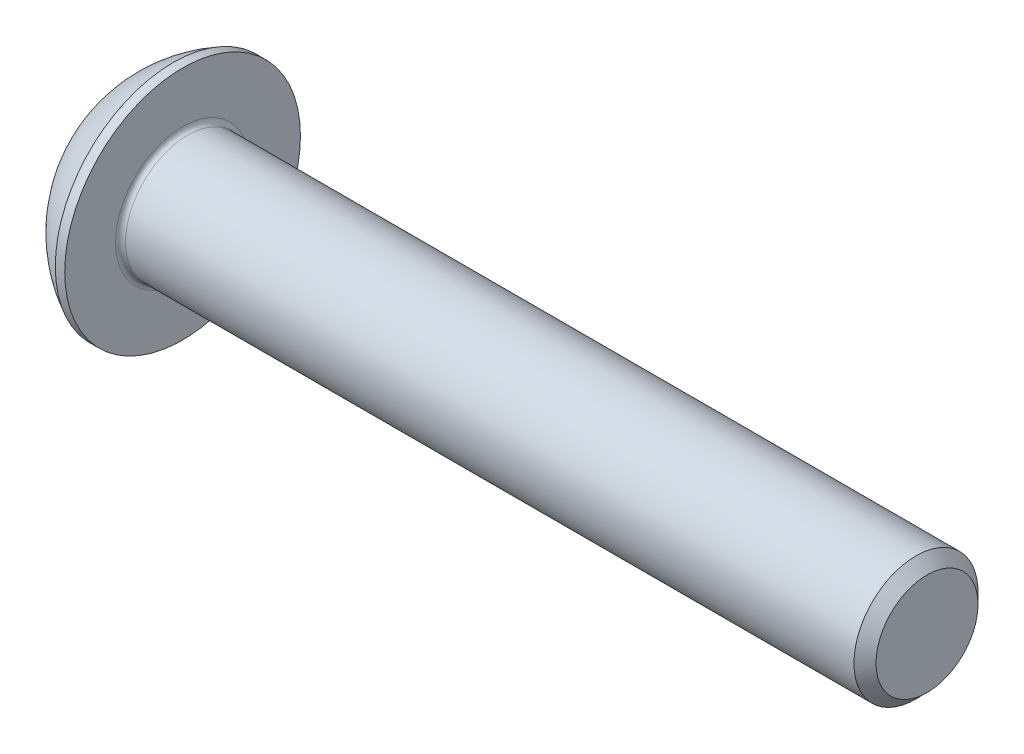
SolidWorks part; units mm, degrees
ref_plane "Plane1" through (0, 0, 0) normal (0, 0, 1) x (1, 0, 0)
ref_plane "Plane2" through (0, 0, 0) normal (0, 1, 0) x (1, 0, 0)
ref_plane "Plane3" through (0, 0, 0) normal (1, 0, 0) x (0, 0, -1)
sketch "BodySke" plane through (0, 0, 0) normal (0, 0, 1) x (1, 0, 0)
  line L0 (32.75, 0) -> (32.75, 2.055)
  line L1 (32.305, 2.5) -> (2.75, 2.5)
  line L2 (2.75, 2.5) -> (2.75, 4.75)
  line L3 (2.75, 4.75) -> (2.37, 4.75)
  line L4 (0, 0) -> (101.6, 0) construction
  line L5 (2.75, -4.75) -> (2.37, -4.75) construction
  line L6 (55.6768, -2.5) -> (2.75, -2.5) construction
  line L7 (32.75, 0) -> (0, 0)
  line L8 (0, 2.375) -> (0, -2.375) construction
  line L9 (0, 0) -> (0, 2.375)
  line L10 (32.75, 2.055) -> (32.305, 2.5)
  line L11 (32.75, -2.055) -> (32.305, -2.5) construction
  line L12 (3.55, 9.525) -> (3.55, -2.5) construction
  line L13 (2.75, 9.525) -> (2.75, -2.5) construction
  arc A1 (0, 2.375) -> (2.37, 4.75) centre (4.755, 0) cw
  dimension "D1" = 4.75
  dimension "Diameter" = 5
  dimension "Length" = 30
  dimension "Head_dia" = 9.5
  dimension "Head_ht" = 2.75
  dimension "Head_side_ht" = 0.38
  dimension "Minor_dia" = 4.11
  dimension "Body_ch_ang" = 45
  dimension "Advance" = 0.8
  dimension "Thread_nom" = 30
revolve "BaseBody" add sketch "BodySke" angle 360 about L4
cosmetic thread "ThreadCosmetic"
fillet "Fillet1" radius 0.2 1 edges at (2.75, 0, 2.5)
sketch "Sketch2" plane through (0, 0, 0) normal (0, 0, 1) x (1, 0, 0)
  line L0 (0, 1.5) -> (1.56, 1.5)
  line L1 (1.56, 1.5) -> (2.426, 0)
  line L3 (2.426, 0) -> (0, 0)
  line L4 (0, 0) -> (0, 1.5)
  line L5 (0, -1.5) -> (1.56, -1.5) construction
  line L6 (0, 0) -> (47.625, 0) construction
  dimension "D2" = 60
  dimension "PreBroach_depth" = 1.56
  dimension "PreBroach_dia" = 3
revolve "PreBroach" cut sketch "Sketch2" angle 360 about L6
sketch "Sketch3" plane through (0, 0, 0) normal (1, 0, 0) x (0, 0, -1)
  line L0 (-1.5, -0.866) -> (-1.5, 0.866)
  line L1 (-1.5, 0.866) -> (0, 1.7321)
  line L2 (0, 1.7321) -> (1.5, 0.866)
  line L3 (1.5, 0.866) -> (1.5, -0.866)
  line L4 (1.5, -0.866) -> (0, -1.7321)
  line L5 (0, -1.7321) -> (-1.5, -0.866)
  dimension "D1" = 1.5
  dimension "D2" = 1.5
  dimension "D3" = 3
  dimension "Hex_size" = 3
extrude "Hex" cut sketch "Sketch3" along normal blind 1.56
sketch "ThdSchSke" plane through (0, 0, 0) normal (0, 0, 1) x (1, 0, 0)
  line L0 (4.35, -2.055) -> (4.0384, -2.5)
  line L1 (4.35, -2.055) -> (4.6616, -2.5)
  line L2 (4.6616, -2.5) -> (4.6616, -3.125)
  line L3 (-3.175, 0) -> (5.1513, 0) construction
  line L5 (4.6616, -3.125) -> (4.0384, -3.125)
  line L6 (4.0384, -3.125) -> (4.0384, -2.5)
  dimension "Thread_minor" = 4.11
  dimension "Diameter" = 5
  dimension "Start" = 4.35
  dimension "SideAngle" = 55
  dimension "VeeAngle" = 70
  dimension "Overcut" = 6.25
revolve "ThreadSchematic" [suppressed] cut sketch "ThdSchSke" angle 360 about L3
pattern_linear "ThdSchPat" [suppressed]
equation "\"D1@BodySke\" = \"Head_dia@BodySke\" * .5"
equation "\"Thread_minor@ThreadCosmetic\" = \"Minor_dia@BodySke\""
equation "\"D1@Sketch3\" = \"Hex_size@Sketch3\" / 2"
equation "\"D2@Sketch3\" = \"D1@Sketch3\""
equation "\"D3@Sketch3\" = \"Hex_size@Sketch3\""
equation "\"Thread_length@ThreadCosmetic\" = ((sgn( (\"Length@BodySke\" - \"Advance@BodySke\" * 2.0) - \"Thread_nom@BodySke\" )-1)*( (\"Length@BodySke\" - \"Advance@BodySke\" * 2.0) - \"Thread_nom@BodySke\" ))/-2+ \"Thread_nom@BodySke\""
equation "\"Thread_minor@ThdSchSke\" = \"Minor_dia@BodySke\""
equation "\"Diameter@ThdSchSke\" = \"Diameter@BodySke\""
equation "\"Overcut@ThdSchSke\" = \"Diameter@BodySke\" * 1.25"
equation "\"Start@ThdSchSke\" = \"Head_ht@BodySke\" + \"Length@BodySke\" - \"Thread_length@ThreadCosmetic\"  '---Non-countersunk---"
equation "\"Num_threads@ThdSchPat\" = int( \"Thread_length@ThreadCosmetic\" / \"Advance@BodySke\" + 0.999 )  + 1"
equation "\"Advance@ThdSchPat\" = \"Thread_length@ThreadCosmetic\" /  (\"Num_threads@ThdSchPat\" - 1) 'relax it"
equation "\"Num_threads@ThdSchPat\" = \"Num_threads@ThdSchPat\" - sgn( \"Num_threads@ThdSchPat\" - 1) '---chamfered tips only---"
